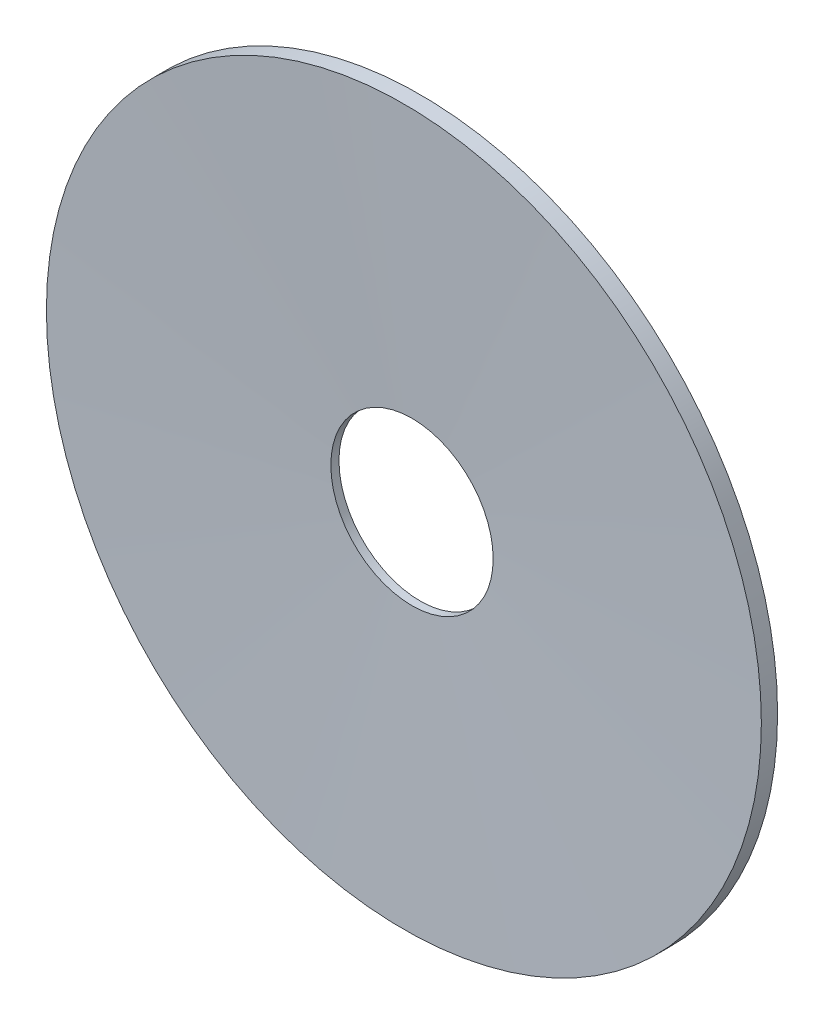
SolidWorks part; units mm, degrees
ref_plane "Front Plane" through (0, 0, 0) normal (0, 0, 1) x (1, 0, 0)
ref_plane "Top Plane" through (0, 0, 0) normal (0, 1, 0) x (1, 0, 0)
ref_plane "Right Plane" through (0, 0, 0) normal (1, 0, 0) x (0, 0, -1)
sketch "Sketch2" plane through (0, 0, 0) normal (0, 0, 1) x (1, 0, 0)
  circle A0 centre (0, 0) radius 89.5 construction
  circle A1 centre (0, 0) radius 88.1
  circle A2 centre (0, 0) radius 85.3 construction
  circle A3 centre (0, 0) radius 20 construction
  circle A4 centre (0, 0) radius 22.8 construction
  dimension "D1" = 179
  dimension "D4" = 40
  dimension "D2" = 1.4
  dimension "D3" = 2.8
  dimension "D5" = 2.8
extrude "Boss-Extrude1" add sketch "Sketch2" along normal blind 4
sketch "Sketch4" plane through (0, 0, 0) normal (0, 1, 0) x (1, 0, 0)
  line L0 (0, -1.8049) -> (0, -4)
  line L1 (0, -4) -> (-88.1, -4)
  line L2 (-88.1, -4) -> (-20, -2)
  line L3 (-20, -2) -> (-20, 0)
  line L4 (-20, 0) -> (0, 0)
  line L5 (0, 0) -> (0, -1.8049)
  line L6 (-88.1, -4) -> (88.1, -4) construction
  point P3 (-8.9867, 0)
  point P8 (0, 0)
  point P9 (0, 0)
  point P10 (0, 0)
  point P11 (0, -3.0153)
  point P14 (0, 0)
  point P15 (0, 0)
  point P16 (0, 0)
  point P20 (0, 0)
  point P21 (-68.4501, -4)
  point P24 (0, 0)
  point P25 (-79.7941, -4)
  point P26 (0, 0)
  dimension "D1" = 2
revolve "Cut-Revolve1" cut sketch "Sketch4" angle 360 about L0
